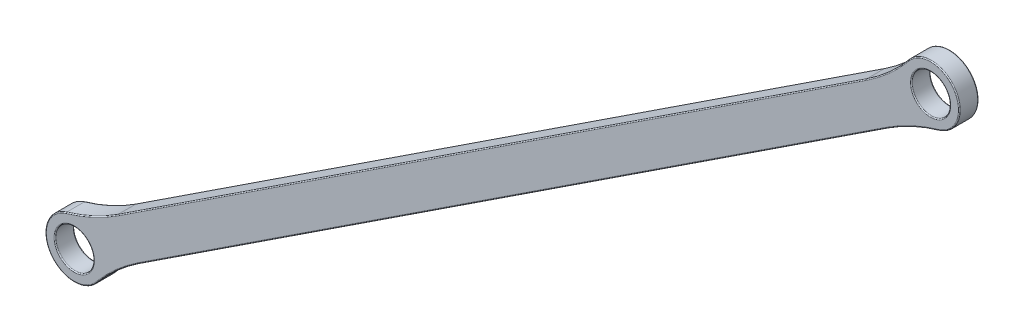
SolidWorks part; units mm, degrees
material "AISI 1020"
ref_plane "Front Plane" through (0, 0, 0) normal (0, 0, 1) x (1, 0, 0)
ref_plane "Top Plane" through (0, 0, 0) normal (0, 1, 0) x (1, 0, 0)
ref_plane "Right Plane" through (0, 0, 0) normal (1, 0, 0) x (0, 0, -1)
sketch "Sketch1" plane through (0, 0, 0) normal (0, 0, 1) x (1, 0, 0)
  line L0 (-91.128, 225.2719) -> (-224.864, 137.4385) construction
  line L1 (-91.128, 225.2719) -> (-224.864, 137.4385) construction
  line L2 (-224.864, 137.4385) -> (-91.128, 225.2719) construction
  line L3 (-226.5108, 139.946) -> (-92.7749, 227.7794)
  line L4 (-223.2171, 134.9309) -> (-89.4812, 222.7643)
  arc A0 (-226.5108, 139.946) -> (-223.2171, 134.9309) centre (-224.864, 137.4385) ccw
  arc A1 (-89.4812, 222.7643) -> (-92.7749, 227.7794) centre (-91.128, 225.2719) ccw
  circle A2 centre (-91.128, 225.2719) radius 4.5
  circle A3 centre (-224.864, 137.4385) radius 4.5
  arc A4 (-89.4812, 222.7643) -> (-92.7749, 227.7794) centre (-91.128, 225.2719) cw
  arc A5 (-226.5108, 139.946) -> (-223.2171, 134.9309) centre (-224.864, 137.4385) cw
  point P3 (-157.996, 181.3552)
  dimension "D2" = 9
  dimension "D1" = 6
extrude "Boss-Extrude1" add sketch "Sketch1" against normal blind 3 contours L4 A2 L3 A1 | L4 A4 L3 A2 | L3 A3 L4 A0 | L3 A5 L4 A3 | A3 L4 A2 L3
fillet "Fillet1" radius 30 4 edges at (-220.4136, 136.7722, -1.5) (-92.2847, 220.9231, -1.5) (-223.7073, 141.7873, -1.5) (-95.5784, 225.9382, -1.5)
fillet "Fillet2" radius 0.15 20 edges at (-221.864, 137.4385, -3) (-221.864, 137.4385, 0) (-88.128, 225.2719, -3) (-88.128, 225.2719, 0) (-218.3237, 137.7525, -3) (-218.3237, 137.7525, 0) (-156.3491, 178.8476, 0) (-156.3491, 178.8476, -3) (-94.0146, 219.3947, -3) (-94.0146, 219.3947, 0) (-87.3667, 227.7422, 0) (-87.3667, 227.7422, -3) (-97.6683, 224.9579, -3) (-97.6683, 224.9579, 0) (-159.6429, 183.8627, -3) (-159.6429, 183.8627, 0) (-221.9774, 143.3157, -3) (-221.9774, 143.3157, 0) (-228.6253, 134.9682, -3) (-228.6253, 134.9682, 0)
